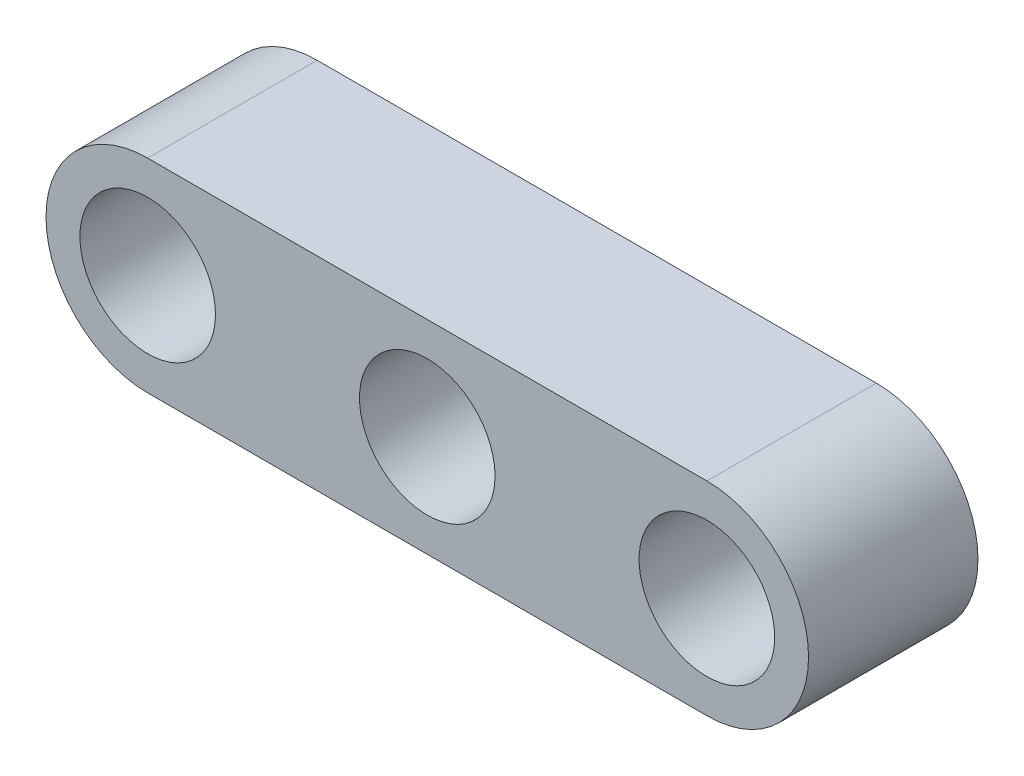
SolidWorks part; units mm, degrees
ref_plane "Front Plane" through (0, 0, 0) normal (0, 0, 1) x (1, 0, 0)
ref_plane "Top Plane" through (0, 0, 0) normal (0, 1, 0) x (1, 0, 0)
ref_plane "Right Plane" through (0, 0, 0) normal (1, 0, 0) x (0, 0, -1)
sketch "Sketch1" plane through (0, 0, 0) normal (0, 0, 1) x (1, 0, 0)
  line L0 (-11.8163, 0) -> (4.6837, 0) construction
  line L1 (-11.8163, 3) -> (4.6837, 3)
  line L2 (-11.8163, -3) -> (4.6837, -3)
  arc A0 (-11.8163, 3) -> (-11.8163, -3) centre (-11.8163, 0) ccw
  arc A1 (4.6837, -3) -> (4.6837, 3) centre (4.6837, 0) ccw
  circle A2 centre (-11.8163, 0) radius 2
  circle A3 centre (4.6837, 0) radius 2
  circle A4 centre (-3.5663, 0) radius 2
  point P3 (-3.5663, 0)
  dimension "D1" = 16.5
extrude "Boss-Extrude1" add sketch "Sketch1" along normal blind 5
